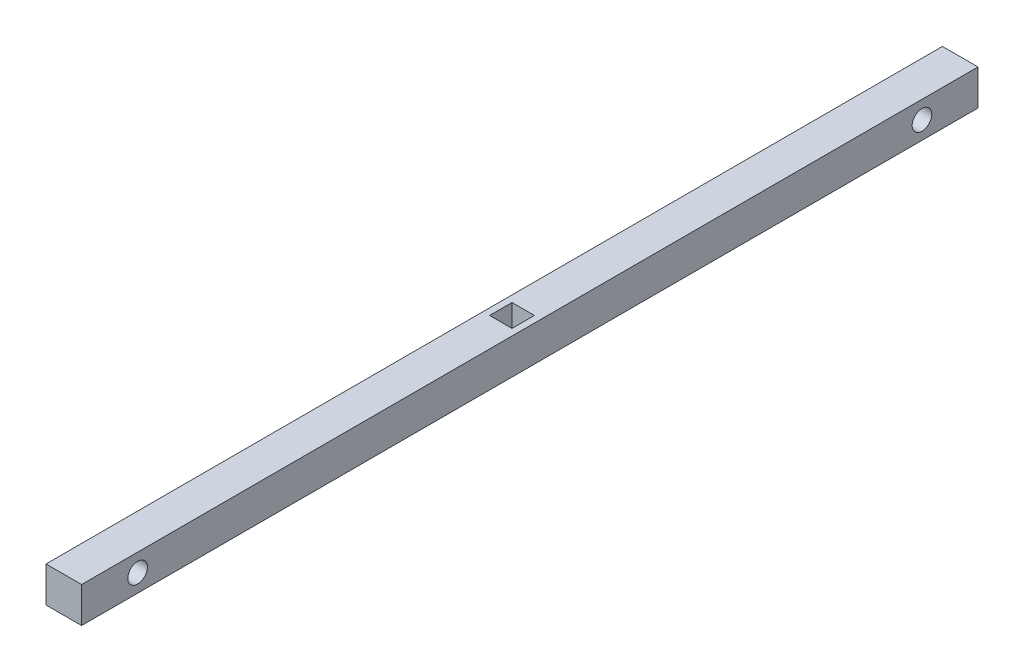
SolidWorks part; units mm, degrees
ref_plane "Front Plane" through (0, 0, 0) normal (0, 0, 1) x (1, 0, 0)
ref_plane "Top Plane" through (0, 0, 0) normal (0, 1, 0) x (1, 0, 0)
ref_plane "Right Plane" through (0, 0, 0) normal (1, 0, 0) x (0, 0, -1)
sketch "Sketch1" plane through (0, 0, 0) normal (0, 0, 1) x (1, 0, 0)
  line L0 (-3.175, 3.175) -> (-3.175, -3.175) construction
  line L1 (-3.175, 3.175) -> (3.175, 3.175) construction
  line L2 (-3.175, 0) -> (0, 0) construction
  line L3 (0, 0) -> (0, 3.175) construction
  dimension "Thickness" = 6.35
  dimension "Width" = 6.35
ref_plane "Plane1" through (-3.175, 3.175, 0) normal (0, -1, 0) x (-1, 0, 0)
sketch "Sketch2" plane through (-3.175, 3.175, 0) normal (0, 1, 0) x (1, 0, 0)
  line L0 (3.175, -609.6) -> (3.175, 609.6) construction
  point P2 (3.175, -596.9)
  point P3 (3.175, 596.9)
  dimension "Length" = 1219.2
  dimension "D1" = 12.7
  dimension "D2" = 12.7
sketch "Sketch3" plane through (0, 0, 0) normal (0, 0, 1) x (1, 0, 0)
  line L1 (-3.175, -3.175) -> (3.175, -3.175)
  line L2 (-3.175, -3.175) -> (-3.175, 3.175)
  line L3 (-3.175, 3.175) -> (3.175, 3.175)
  line L4 (3.175, -3.175) -> (3.175, 3.175)
  line L5 (0, 3.175) -> (0, -3.175) construction
  line L6 (-3.175, 0) -> (3.175, 0) construction
  line L7 (-3.175, 0) -> (0, 0) construction
extrude "Boss-Extrude1" add sketch "Sketch3" along normal up to vertex (609.6 mm away) and the other way up to vertex (609.6 mm away) up to point (0, 3.175, 609.6) other way up to point (0, 3.175, -609.6)
ref_plane "Plane2" through (0, 0, -449.6) normal (0, 0, -1) x (-1, 0, 0)
sketch "Sketch4" plane through (0, 0, -449.6) normal (0, 0, -1) x (-1, 0, 0)
  line L0 (-3.175, -3.175) -> (-3.175, 3.175) construction
  line L1 (-3.675, 3.675) -> (3.675, 3.675)
  line L2 (-3.675, 3.675) -> (-3.675, -3.675)
  line L3 (-3.675, -3.675) -> (3.675, -3.675)
  line L4 (3.675, 3.675) -> (3.675, -3.675)
  line L5 (-3.675, 3.675) -> (3.675, -3.675) construction
  line L6 (-3.675, -3.675) -> (3.675, 3.675) construction
  point P0 (0, 0)
  dimension "D1" = 0.5
extrude "Cut-Extrude1" cut sketch "Sketch4" against normal through all
sketch "Sketch5" plane through (3.175, 0, 0) normal (-1, 0, 0) x (0, 1, 0)
  line L2 (3.175, 449.6) -> (3.175, 609.6) construction
  line L3 (-3.175, 449.6) -> (3.175, 449.6) construction
  line L4 (3.175, 609.6) -> (-3.175, 609.6) construction
  circle A0 centre (0, 599.6) radius 1.75
  circle A1 centre (0, 459.6) radius 1.75
  dimension "D2" = 3.5
  dimension "D1" = 10
  dimension "D3" = 10
  dimension "D4" = 3.175
extrude "Cut-Extrude2" cut sketch "Sketch5" along normal through all
sketch "Sketch6" plane through (0, 3.175, 0) normal (0, 1, 0) x (1, 0, 0)
  line L0 (3.175, 449.6) -> (3.175, 609.6) construction
  line L1 (-3.175, 449.6) -> (3.175, 449.6) construction
  line L3 (-2, 531.6) -> (2, 531.6)
  line L4 (-2, 531.6) -> (-2, 527.6)
  line L5 (-2, 527.6) -> (2, 527.6)
  line L6 (2, 531.6) -> (2, 527.6)
  line L7 (-2, 531.6) -> (2, 527.6) construction
  line L8 (-2, 527.6) -> (2, 531.6) construction
  circle A0 centre (0, 529.6) radius 2 construction
  dimension "D1" = 4
  dimension "D2" = 3.175
  dimension "D3" = 80
extrude "Cut-Extrude3" cut sketch "Sketch6" against normal through all
equation "\"D1@Sketch2\"=\"Width@Sketch1\"*2"
equation "\"D2@Sketch2\"=\"D1@Sketch2\""
